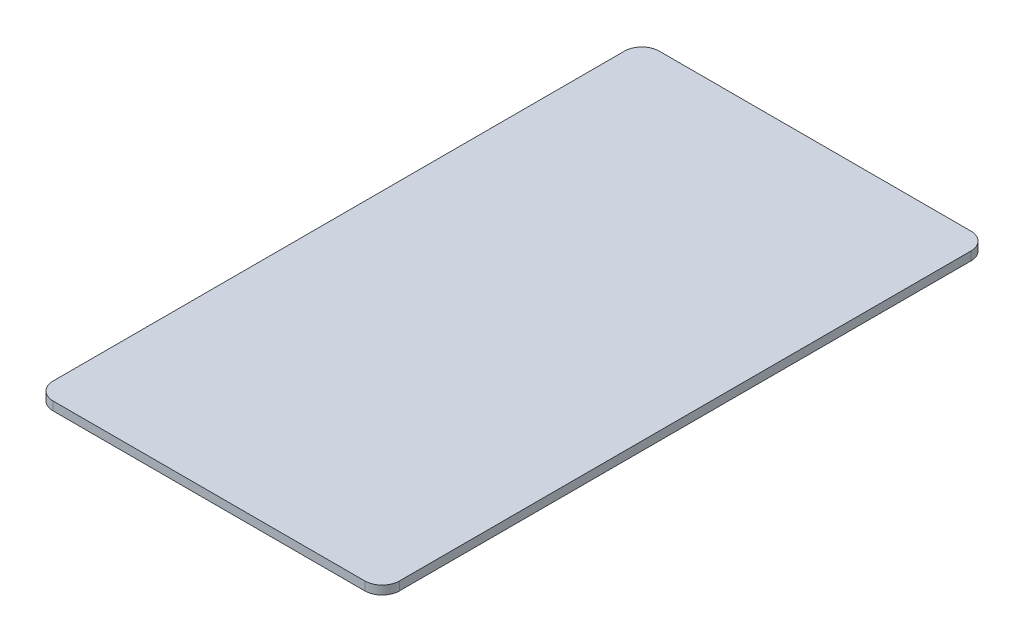
SolidWorks part; units mm, degrees
material "6061-T6 (SS)"
ref_plane "Front Plane" through (0, 0, 0) normal (0, 0, 1) x (1, 0, 0)
ref_plane "Top Plane" through (0, 0, 0) normal (0, 1, 0) x (1, 0, 0)
ref_plane "Right Plane" through (0, 0, 0) normal (1, 0, 0) x (0, 0, -1)
sketch "Sketch1" plane through (0, 0, 0) normal (0, 1, 0) x (1, 0, 0)
  line L1 (-20, -35) -> (20, -35)
  line L2 (-20, -35) -> (-20, 35)
  line L3 (-20, 35) -> (20, 35)
  line L4 (20, -35) -> (20, 35)
  line L5 (-20, -35) -> (20, 35) construction
  line L6 (-20, 35) -> (20, -35) construction
  point P0 (0, 0)
  dimension "D1" = 70
  dimension "D2" = 40
extrude "Boss-Extrude1" add sketch "Sketch1" along normal blind 1
fillet "Fillet1" radius 2 4 edges at (20, 0.5, 35) (-20, 0.5, 35) (20, 0.5, -35) (-20, 0.5, -35)
